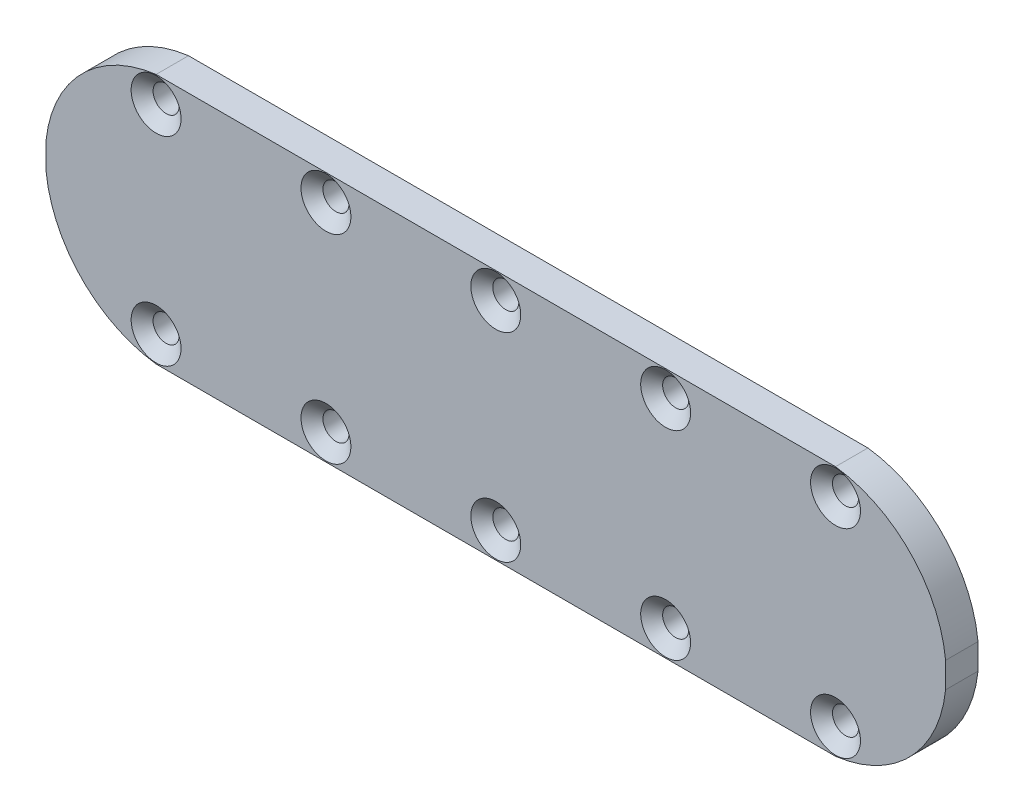
SolidWorks part; units mm, degrees
ref_plane "Front" through (0, 0, 0) normal (0, 0, 1) x (1, 0, 0)
ref_plane "Top" through (0, 0, 0) normal (0, 1, 0) x (1, 0, 0)
ref_plane "Right" through (0, 0, 0) normal (1, 0, 0) x (0, 0, -1)
sketch "Sketch1" plane through (0, 0, 0) normal (0, 0, 1) x (1, 0, 0)
  line L1 (88.138, 24.5745) -> (-88.138, 24.5745)
  line L2 (88.138, 24.5745) -> (88.138, -24.5745)
  line L3 (88.138, -24.5745) -> (-88.138, -24.5745)
  line L4 (-88.138, 24.5745) -> (-88.138, -24.5745)
  line L5 (88.138, 24.5745) -> (-88.138, -24.5745) construction
  line L6 (88.138, -24.5745) -> (-88.138, 24.5745) construction
  point P0 (0, 0)
  dimension "D1" = 176.276
  dimension "D2" = 49.149
extrude "Boss-Extrude1" add sketch "Sketch1" along normal blind 6.35
sketch "Sketch22" plane through (0, 0, 6.35) normal (0, 0, 1) x (1, 0, 0)
  line L0 (-63.5, 0) -> (63.5, 0) construction
  line L1 (-63.5, 14.351) -> (63.5, 14.351)
  line L2 (-63.5, -14.351) -> (63.5, -14.351)
  line L6 (-63.5, 24.765) -> (63.5, 24.765)
  line L7 (-63.5, -24.765) -> (63.5, -24.765)
  arc A0 (-63.5, 14.351) -> (-63.5, -14.351) centre (-63.5, 0) ccw
  arc A1 (63.5, -14.351) -> (63.5, 14.351) centre (63.5, 0) ccw
  arc A4 (63.5, -24.765) -> (63.5, 24.765) centre (63.5, 0) ccw
  arc A5 (-63.5, 24.765) -> (-63.5, -24.765) centre (-63.5, 0) ccw
  point P2 (0, 0)
  line M5 (-88.138, 24.5745) -> (-88.138, -24.5745)
  line M6 (-88.138, -24.5745) -> (88.138, -24.5745)
  line M7 (88.138, -24.5745) -> (88.138, 24.5745)
  line M8 (88.138, 24.5745) -> (-88.138, 24.5745)
  dimension "D1" = 127
  dimension "D2" = 28.702
  dimension "D3" = 10.414
extrude "Cut-Extrude3" cut sketch "Sketch22" against normal through all contours A5 M8 M5 | A5 M5 M6 | A4 M6 M7 | A4 M7 M8
sketch "Sketch27" plane through (0, 0, 6.35) normal (0, 0, 1) x (1, 0, 0)
  point P0 (0, 19.4945)
  point P1 (-66.5658, 19.4945)
  point P4 (-33.2829, 19.4945)
  point P6 (0, -19.4945)
  point P7 (66.5658, 19.4945)
  point P8 (66.5658, -19.4945)
  point P10 (-66.5658, -19.4945)
  point P13 (33.2829, 19.4945)
  point P14 (33.2829, -19.4945)
  point P15 (-33.2829, -19.4945)
hole_wizard "CSK for #10 Flat Head Machine Screw (100)1" positions "Sketch28" profile "Sketch29" countersink size "#10" standard "ANSI Inch" end condition through all
sketch "Sketch28" plane through (0, 0, 6.35) normal (0, 0, 1) x (1, 0, 0)
  point P0 (-66.5658, 19.4945)
  point P3 (-33.2829, 19.4945)
  point P6 (0, 19.4945)
  point P9 (33.2829, 19.4945)
  point P12 (66.5658, 19.4945)
  point P15 (66.5658, -19.4945)
  point P18 (33.2829, -19.4945)
  point P21 (0, -19.4945)
  point P24 (-33.2829, -19.4945)
  point P27 (-66.5658, -19.4945)
sketch "Sketch29" plane through (-66.5658, 19.4945, 6.35) normal (1, 0, 0) x (0, -1, 0)
  line L0 (0, 0) -> (0, 6.35)
  line L1 (0, 6.35) -> (2.5527, 6.35)
  line L2 (2.5527, 6.35) -> (2.5527, 1.9608)
  line L3 (2.5527, 1.9608) -> (4.8895, 0)
  line L5 (4.8895, 0) -> (0, 0)
  line L6 (-2.5527, 1.9608) -> (-4.8895, 0) construction
  line L11 (0, -6.35) -> (0, 107.95) construction
  dimension "Thru Hole Dia." = 5.1054
  dimension "Thru Hole Depth" = 6.35
  dimension "Near C'Sink Dia." = 9.779
  dimension "Near C'Sink Angle" = 100
